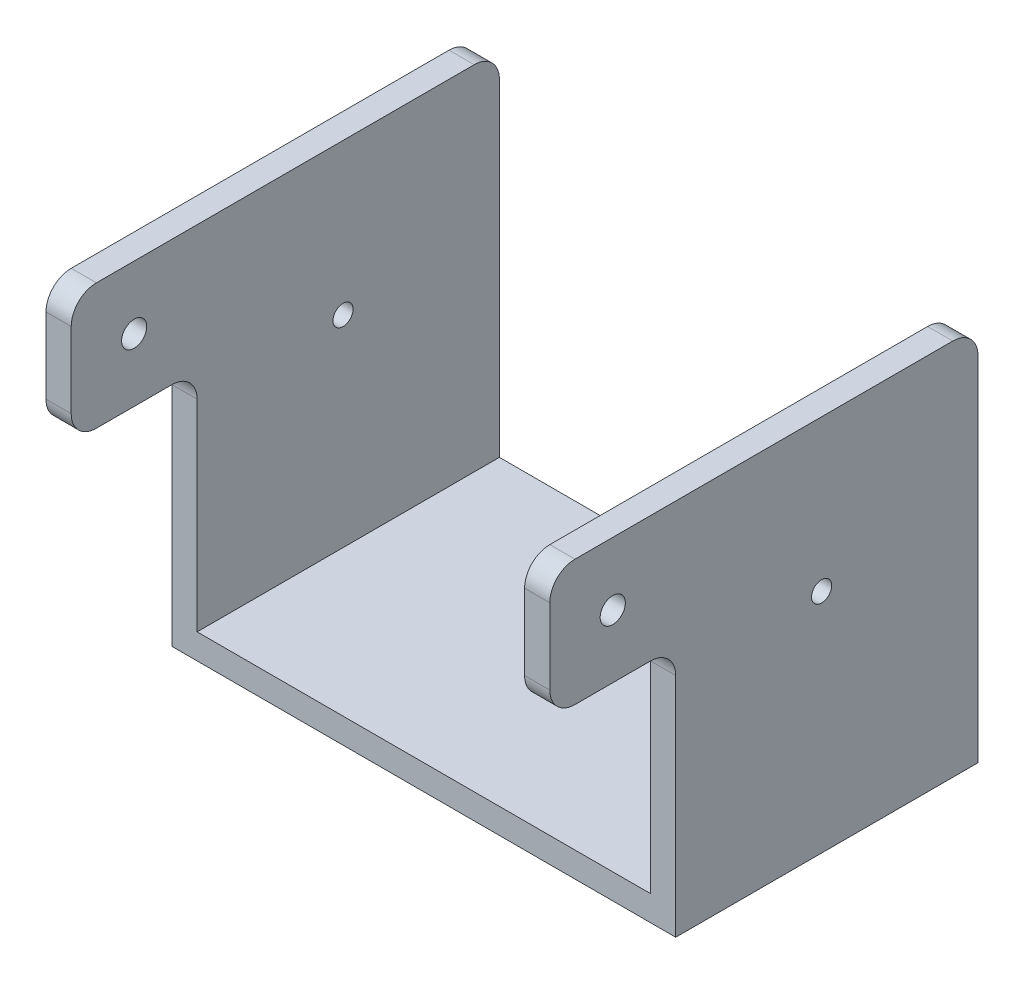
SolidWorks part; units mm, degrees
ref_plane "Front Plane" through (0, 0, 0) normal (0, 0, 1) x (1, 0, 0)
ref_plane "Top Plane" through (0, 0, 0) normal (0, 1, 0) x (1, 0, 0)
ref_plane "Right Plane" through (0, 0, 0) normal (1, 0, 0) x (0, 0, -1)
sketch "Sketch1" plane through (0, 0, 0) normal (0, 0, 1) x (1, 0, 0)
  line L0 (0, 0) -> (200, 0)
  line L1 (200, 0) -> (200, 150)
  line L2 (200, 150) -> (190, 150)
  line L3 (190, 150) -> (190, 10)
  line L4 (190, 10) -> (10, 10)
  line L5 (10, 10) -> (10, 150)
  line L6 (10, 150) -> (0, 150)
  line L7 (0, 150) -> (0, 0)
  dimension "D1" = 200
  dimension "D2" = 10
  dimension "D3" = 10
  dimension "D4" = 10
  dimension "D5" = 150
  dimension "D6" = 150
extrude "Boss-Extrude1" add sketch "Sketch1" along normal blind 120
sketch "Sketch2" plane through (0, 0, 120) normal (0, 0, 1) x (1, 0, 0)
  line L0 (10, 10) -> (10, 150) construction
  line L1 (200, 0) -> (200, 150) construction
  line L2 (0, 150) -> (10, 150)
  line L3 (0, 150) -> (0, 100)
  line L4 (0, 100) -> (10, 100)
  line L5 (10, 150) -> (10, 100)
  line L6 (190, 150) -> (200, 150)
  line L7 (190, 150) -> (190, 100)
  line L8 (190, 100) -> (200, 100)
  line L9 (200, 150) -> (200, 100)
  dimension "D1" = 50
  dimension "D2" = 50
extrude "Boss-Extrude2" add sketch "Sketch2" along normal blind 50
sketch "Sketch3" plane through (0, 0, 0) normal (-1, 0, 0) x (0, 0, 1)
  line L0 (170, 150) -> (170, 100) construction
  line L1 (170, 100) -> (120, 100) construction
  circle A0 centre (145, 125) radius 5
  dimension "D1" = 10
  dimension "D2" = 25
  dimension "D3" = 25
extrude "Cut-Extrude1" cut sketch "Sketch3" against normal blind 200
fillet "Fillet1" radius 10 8 edges at (195, 150, 170) (195, 100, 170) (195, 100, 120) (5, 100, 120) (5, 100, 170) (5, 150, 170) (5, 150, 0) (195, 150, 0)
sketch "Sketch5" plane through (0, 0, 0) normal (-1, 0, 0) x (0, 0, 1)
  circle A0 centre (145, 125) radius 60
  circle A1 centre (62.0844, 90) radius 30
  circle A2 centre (62.0844, 90) radius 4
  point P6 (62.0844, 90)
  dimension "D1" = 120
  dimension "D2" = 60
  dimension "D3" = 90
  dimension "D4" = 35
extrude "Cut-Extrude2" cut sketch "Sketch5" against normal blind 200 contours A2
sketch "Sketch6" plane through (0, 0, 0) normal (0, -1, 0) x (1, 0, 0)
  line L2 (0, 120) -> (200, 120) construction
  line L3 (0, 120) -> (0, 0) construction
  circle A0 centre (100, 60) radius 12.5
  circle A1 centre (100, 60) radius 5
  dimension "D3" = 25
  dimension "D1" = 60
  dimension "D2" = 100
extrude "Boss-Extrude3" add sketch "Sketch6" along normal blind 20 contours A0 | A1
sketch "Sketch7" plane through (0, 0, 0) normal (1, 0, 0) x (0, 0, -1)
  line L0 (-72.5, 0) -> (-47.5, 0) construction
  line L1 (-47.5, -20) -> (-47.5, 0) construction
  circle A0 centre (-60, -10) radius 3
  dimension "D1" = 10
  dimension "D2" = 12.5
extrude "Cut-Extrude3" cut sketch "Sketch7" along normal blind 12.5 and the other way blind 12.5 from offset 100
